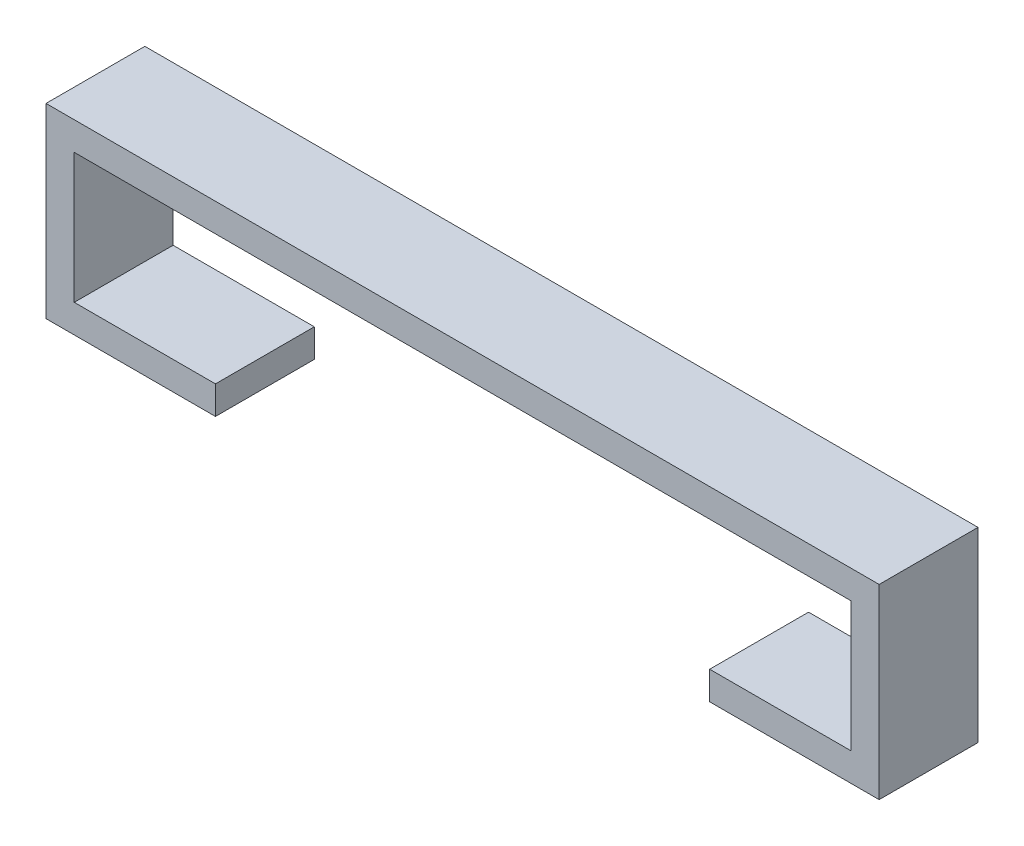
SolidWorks part; units mm, degrees
ref_plane "Front Plane" through (0, 0, 0) normal (0, 0, 1) x (1, 0, 0)
ref_plane "Top Plane" through (0, 0, 0) normal (0, 1, 0) x (1, 0, 0)
ref_plane "Right Plane" through (0, 0, 0) normal (1, 0, 0) x (0, 0, -1)
sketch "Sketch1" plane through (0, 0, 0) normal (0, 0, 1) x (1, 0, 0)
  line L0 (0, -12.4823) -> (0, 50.6383) construction
  line L1 (-29.5, 13.2) -> (29.5, 13.2)
  line L2 (29.5, 13.2) -> (29.5, 0)
  line L3 (29.5, 0) -> (17.5, 0)
  line L4 (17.5, 0) -> (17.5, 2)
  line L5 (17.5, 2) -> (27.5, 2)
  line L6 (27.5, 2) -> (27.5, 11.2)
  line L7 (27.5, 11.2) -> (-27.5, 11.2)
  line L9 (-27.5, 2) -> (-27.5, 11.2)
  line L10 (-17.5, 2) -> (-27.5, 2)
  line L11 (-17.5, 0) -> (-17.5, 2)
  line L12 (-29.5, 0) -> (-17.5, 0)
  line L13 (-29.5, 13.2) -> (-29.5, 0)
  dimension "D1" = 9.2
  dimension "D2" = 55
  dimension "D3" = 10
  dimension "D4" = 2
  dimension "D5" = 2
  dimension "D6" = 2
extrude "Boss-Extrude1" add sketch "Sketch1" along normal blind 7
equation "\"D1@Sketch1\"=7.20mm+2"
